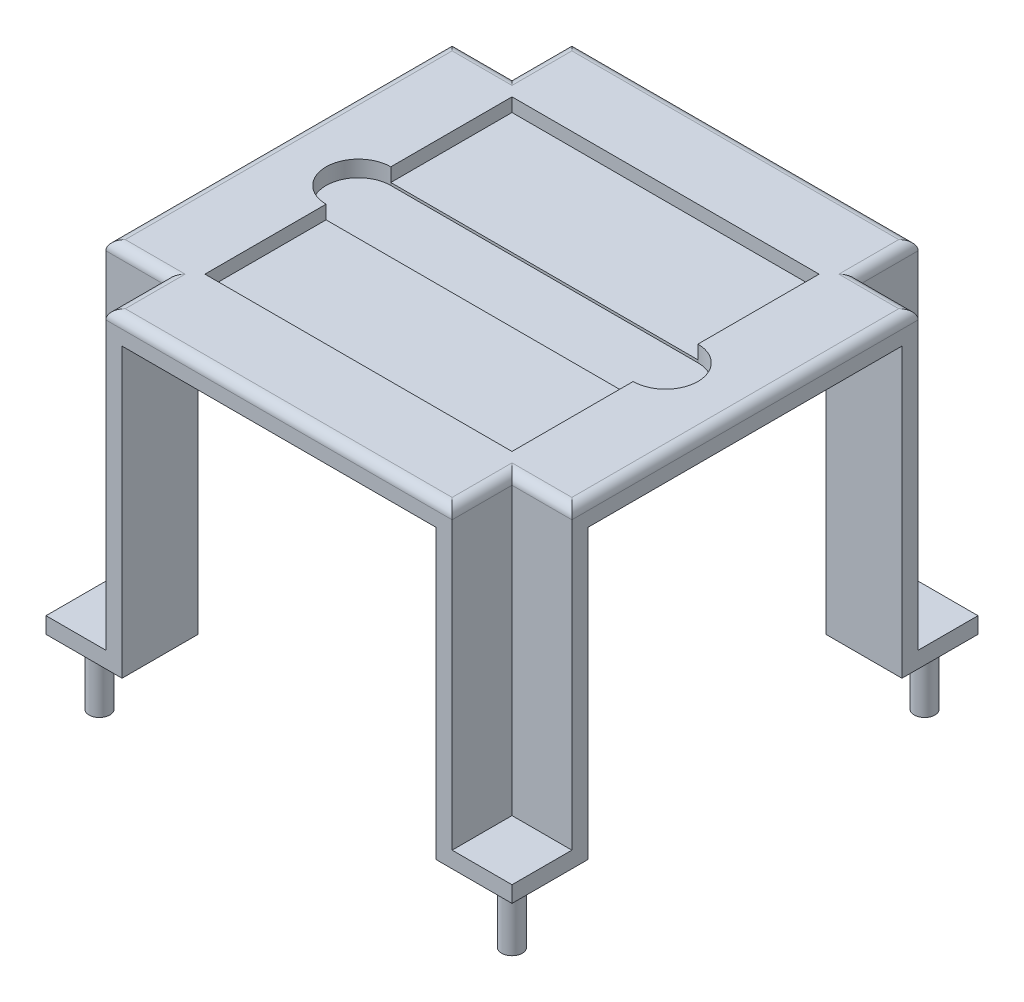
SolidWorks part; units mm, degrees
ref_plane "Front Plane" through (0, 0, 0) normal (0, 0, 1) x (1, 0, 0)
ref_plane "Top Plane" through (0, 0, 0) normal (0, 1, 0) x (1, 0, 0)
ref_plane "Right Plane" through (0, 0, 0) normal (1, 0, 0) x (0, 0, -1)
sketch "Sketch1" plane through (0, 0, 0) normal (0, 1, 0) x (1, 0, 0)
  line L0 (-16.2398, 0) -> (0, 0) construction
  line L59 (-72, 72) -> (72, 72) construction
  line L60 (-72, 72) -> (-72, -72) construction
  line L77 (-72, -72) -> (72, -72) construction
  line L78 (72, 72) -> (72, -72) construction
  line L79 (0, 0) -> (0, -18.6636) construction
  line L80 (-72, 53.5) -> (-53.5, 53.5)
  line L81 (-63.75, 63.75) -> (63.75, 63.75) construction
  line L82 (-63.75, 63.75) -> (-63.75, -63.75) construction
  line L83 (-63.75, -63.75) -> (63.75, -63.75) construction
  line L84 (63.75, 63.75) -> (63.75, -63.75) construction
  line L85 (-53.5, 72) -> (-53.5, 53.5)
  line L86 (-72, 72) -> (-53.5, 72)
  line L87 (-40.5, 51) -> (40.5, 51) construction
  line L88 (-40.5, 51) -> (-40.5, -51) construction
  line L89 (-40.5, -51) -> (40.5, -51) construction
  line L90 (40.5, 51) -> (40.5, -51) construction
  line L91 (-72, -72) -> (-53.5, -72)
  line L92 (-72, -72) -> (-72, -53.5)
  line L93 (-72, -53.5) -> (-53.5, -53.5)
  line L94 (-53.5, -72) -> (-53.5, -53.5)
  line L107 (-72, 72) -> (-72, 53.5)
  line L108 (72, -53.5) -> (53.5, -53.5)
  line L109 (53.5, -72) -> (53.5, -53.5)
  line L110 (72, -72) -> (53.5, -72)
  line L111 (72, -72) -> (72, -53.5)
  line L112 (72, 72) -> (72, 53.5)
  line L113 (72, 72) -> (53.5, 72)
  line L114 (53.5, 72) -> (53.5, 53.5)
  line L115 (72, 53.5) -> (53.5, 53.5)
  point P0 (0, 0)
  point P5 (0, 0)
  point P10 (0, 0)
  dimension "D1" = 144
  dimension "D2" = 127.5
extrude "Boss-Extrude1" add sketch "Sketch1" along normal blind 5
sketch "Sketch2" plane through (0, 0, 0) normal (0, -1, 0) x (1, 0, 0)
  line L0 (-72, -53.5) -> (-72, -48.5)
  line L1 (-63.75, 63.75) -> (63.75, 63.75) construction
  line L2 (-63.75, 63.75) -> (-63.75, -63.75) construction
  line L3 (-63.75, -63.75) -> (63.75, -63.75) construction
  line L4 (63.75, 63.75) -> (63.75, -63.75) construction
  line L5 (-63.75, 63.75) -> (63.75, -63.75) construction
  line L6 (-63.75, -63.75) -> (63.75, 63.75) construction
  line L7 (-72, -48.5) -> (-48.5, -48.5)
  line L9 (-53.5, -72) -> (-48.5, -72)
  line L10 (-48.5, -72) -> (-48.5, -48.5)
  line L11 (-72, -53.5) -> (-53.5, -53.5)
  line L12 (-53.5, -53.5) -> (-53.5, -72)
  line L13 (-17.6666, 0) -> (0, 0) construction
  line L14 (0, 0) -> (0, -19.5271) construction
  line L15 (-72, 53.5) -> (-53.5, 53.5)
  line L16 (-72, 53.5) -> (-72, 48.5)
  line L17 (-72, 48.5) -> (-48.5, 48.5)
  line L18 (-48.5, 72) -> (-48.5, 48.5)
  line L19 (-53.5, 72) -> (-48.5, 72)
  line L20 (-53.5, 53.5) -> (-53.5, 72)
  line L21 (72, -53.5) -> (53.5, -53.5)
  line L22 (72, -53.5) -> (72, -48.5)
  line L23 (72, -48.5) -> (48.5, -48.5)
  line L24 (48.5, -72) -> (48.5, -48.5)
  line L25 (53.5, -72) -> (48.5, -72)
  line L26 (53.5, -53.5) -> (53.5, -72)
  line L27 (72, 53.5) -> (72, 48.5)
  line L28 (72, 48.5) -> (48.5, 48.5)
  line L29 (48.5, 72) -> (48.5, 48.5)
  line L30 (53.5, 72) -> (48.5, 72)
  line L31 (53.5, 53.5) -> (53.5, 72)
  line L32 (72, 53.5) -> (53.5, 53.5)
  point P0 (0, 0)
extrude "Boss-Extrude2" add sketch "Sketch2" against normal blind 88.9
sketch "Sketch3" plane through (0, 0, 0) normal (0, -1, 0) x (1, 0, 0)
  line L1 (-63.75, 63.75) -> (63.75, 63.75) construction
  line L2 (-63.75, 63.75) -> (-63.75, -63.75) construction
  line L3 (-63.75, -63.75) -> (63.75, -63.75) construction
  line L4 (63.75, 63.75) -> (63.75, -63.75) construction
  line L5 (-63.75, 63.75) -> (63.75, -63.75) construction
  line L6 (-63.75, -63.75) -> (63.75, 63.75) construction
  circle A0 centre (-63.75, 63.75) radius 3.2
  circle A1 centre (63.75, 63.75) radius 3.2
  circle A2 centre (-63.75, -63.75) radius 3.2
  circle A3 centre (63.75, -63.75) radius 3.2
  point P0 (0, 0)
extrude "Boss-Extrude3" add sketch "Sketch3" along normal blind 20
sketch "Sketch4" plane through (0, 88.9, 0) normal (0, 1, 0) x (1, 0, 0)
  line L0 (-72, 53.5) -> (-72, -53.5)
  line L1 (-72, -53.5) -> (-53.5, -53.5)
  line L2 (-53.5, -53.5) -> (-53.5, -72)
  line L3 (-53.5, -72) -> (53.5, -72)
  line L4 (53.5, -72) -> (53.5, -53.5)
  line L5 (53.5, -53.5) -> (72, -53.5)
  line L6 (72, -53.5) -> (72, 53.5)
  line L7 (72, 53.5) -> (53.5, 53.5)
  line L8 (53.5, 53.5) -> (53.5, 72)
  line L9 (53.5, 72) -> (-53.5, 72)
  line L10 (-53.5, 72) -> (-53.5, 53.5)
  line L11 (-53.5, 53.5) -> (-72, 53.5)
extrude "Boss-Extrude4" add sketch "Sketch4" along normal blind 7.5
fillet "Fillet1" radius 3 12 edges at (-53.5, 96.4, -62.75) (0, 96.4, -72) (53.5, 96.4, -62.75) (62.75, 96.4, -53.5) (72, 96.4, 0) (62.75, 96.4, 53.5) (53.5, 96.4, 62.75) (0, 96.4, 72) (-53.5, 96.4, 62.75) (-62.75, 96.4, 53.5) (-72, 96.4, 0) (-62.75, 96.4, -53.5)
sketch "Sketch5" plane through (0, 96.4, 0) normal (0, 1, 0) x (1, 0, 0)
  line L1 (-47.45, 47.45) -> (47.45, 47.45)
  line L2 (-47.45, 47.45) -> (-47.45, -47.45)
  line L3 (-47.45, -47.45) -> (47.45, -47.45)
  line L4 (47.45, 47.45) -> (47.45, -47.45)
  line L5 (-47.45, 47.45) -> (47.45, -47.45) construction
  line L6 (-47.45, -47.45) -> (47.45, 47.45) construction
  point P0 (0, 0)
extrude "Cut-Extrude1" cut sketch "Sketch5" against normal blind 4.2
sketch "Sketch6" plane through (0, 96.4, 0) normal (0, 1, 0) x (1, 0, 0)
  line L0 (-47.45, 47.45) -> (-47.45, -47.45) construction
  line L1 (47.45, -47.45) -> (47.45, 47.45) construction
  line L2 (-47.45, 10) -> (47.45, 10)
  line L3 (-47.45, -10) -> (47.45, -10)
  arc A0 (-47.45, 10) -> (-47.45, -10) centre (-47.45, 0) ccw
  arc A1 (47.45, -10) -> (47.45, 10) centre (47.45, 0) ccw
extrude "Cut-Extrude2" cut sketch "Sketch6" against normal blind 5
